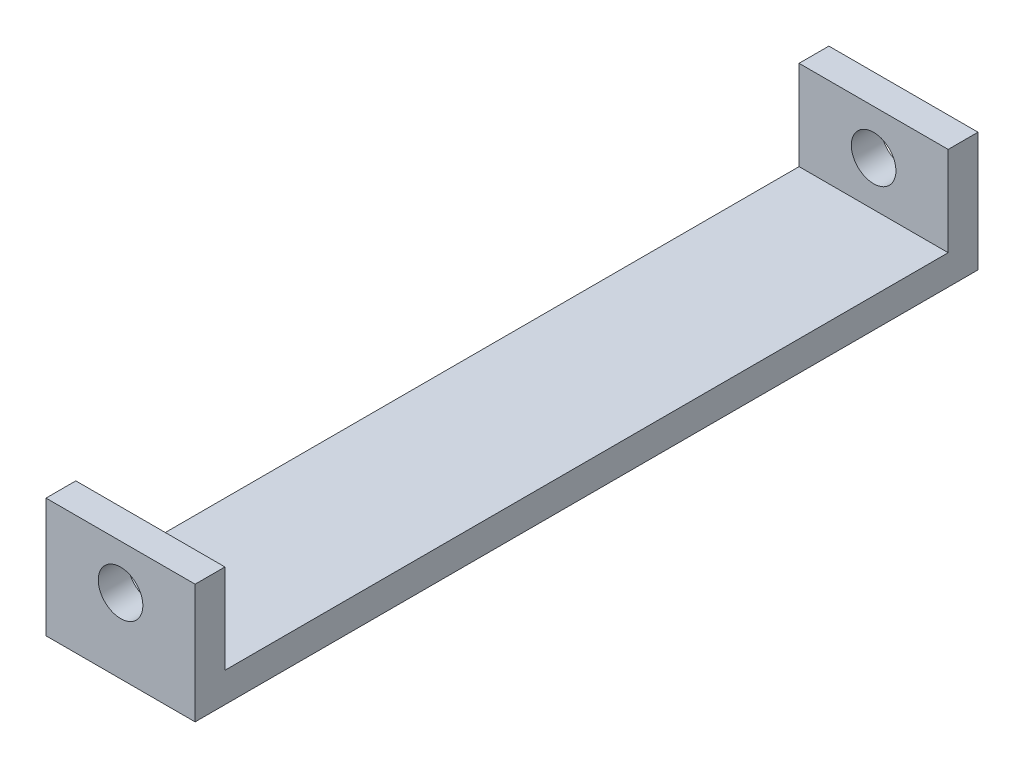
SolidWorks part; units mm, degrees
ref_plane "Front Plane" through (0, 0, 0) normal (0, 0, 1) x (1, 0, 0)
ref_plane "Top Plane" through (0, 0, 0) normal (0, 1, 0) x (1, 0, 0)
ref_plane "Right Plane" through (0, 0, 0) normal (1, 0, 0) x (0, 0, -1)
sketch "Sketch1" plane through (0, 0, 0) normal (1, 0, 0) x (0, 0, -1)
  line L0 (-1.27, 8.128) -> (60.325, 8.128)
  line L3 (60.325, 8.128) -> (60.325, 15.748)
  line L6 (-1.27, 8.128) -> (-1.27, 15.748)
  dimension "D2" = 61.595
  dimension "D3" = 7.62
extrude "Extrude-Thin1" add sketch "Sketch1" along normal blind 12.7 thin
hole_wizard "#6 Clearance Hole1" positions "Sketch3" profile "Sketch2" hole size "#6" standard "ANSI Inch"
sketch "Sketch3" plane through (0, 0, 1.27) normal (0, 0, -1) x (-1, 0, 0)
  line L0 (-12.7, 15.748) -> (0, 15.748) construction
  line L1 (0, 8.128) -> (0, 15.748) construction
  point P0 (-6.35, 11.938)
  dimension "D1" = 3.81
  dimension "D2" = 6.35
sketch "Sketch2" plane through (6.35, 11.938, 1.27) normal (1, 0, 0) x (0, 1, 0)
  line L0 (0, 0) -> (0, 8.7608)
  line L1 (0, 8.7608) -> (1.8986, 7.62)
  line L2 (1.8986, 7.62) -> (1.8986, 0)
  line L5 (1.8986, 0) -> (0, 0)
  line L10 (0, 8.7608) -> (-1.8986, 7.62) construction
  line L11 (0, -6.35) -> (0, 107.95) construction
  dimension "Hole Dia." = 3.7973
  dimension "Hole Depth" = 7.62
  dimension "Drill Angle" = 118
hole_wizard "#6 Clearance Hole2" positions "Sketch5" profile "Sketch4" hole size "#6" standard "ANSI Inch"
sketch "Sketch5" plane through (0, 0, -60.325) normal (0, 0, 1) x (1, 0, 0)
  line L0 (12.7, 15.748) -> (0, 15.748) construction
  line L1 (0, 15.748) -> (0, 8.128) construction
  point P0 (6.35, 11.938)
  dimension "D1" = 3.81
  dimension "D2" = 6.35
sketch "Sketch4" plane through (6.35, 11.938, -60.325) normal (1, 0, 0) x (0, -1, 0)
  line L0 (0, 0) -> (0, 8.7608)
  line L1 (0, 8.7608) -> (1.8986, 7.62)
  line L2 (1.8986, 7.62) -> (1.8986, 0)
  line L5 (1.8986, 0) -> (0, 0)
  line L10 (0, 8.7608) -> (-1.8986, 7.62) construction
  line L11 (0, -6.35) -> (0, 107.95) construction
  dimension "Hole Dia." = 3.7973
  dimension "Hole Depth" = 7.62
  dimension "Drill Angle" = 118
